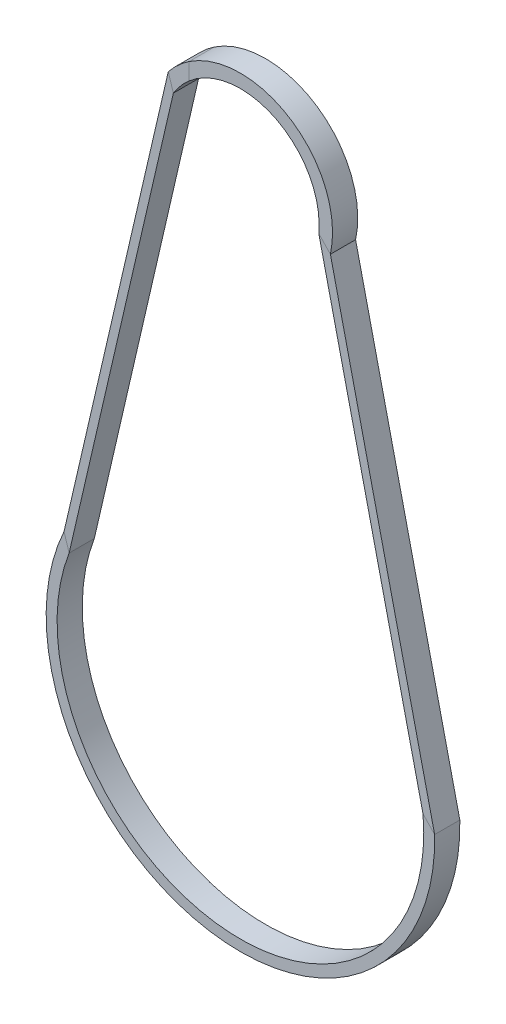
SolidWorks part; units mm, degrees
ref_plane "Front Plane" through (0, 0, 0) normal (0, 0, 1) x (1, 0, 0)
ref_plane "Top Plane" through (0, 0, 0) normal (0, 1, 0) x (1, 0, 0)
ref_plane "Right Plane" through (0, 0, 0) normal (1, 0, 0) x (0, 0, -1)
sketch "Sketch2" plane through (0, 0, 0) normal (0, 0, 1) x (1, 0, 0)
  line L0 (0, 0) -> (1, 0) construction
  line L1 (0, 0) -> (0, 1) construction
  line L2 (10.3864, 8.148) -> (22.7969, -45.48)
  line L3 (-15.8751, -45.48) -> (-3.4646, 8.148)
  arc A0 (-3.4646, 8.148) -> (10.3864, 8.148) centre (3.4609, 6.5453) cw
  arc A1 (22.7969, -45.48) -> (-15.8751, -45.48) centre (3.4609, -49.9547) cw
sketch "Sketch3" plane through (0, 0, 0) normal (0, 0, 1) x (1, 0, 0)
  line L0 (3.4609, 1) -> (3.4609, 13.6538)
  arc A1 (10.3864, 8.148) -> (-3.4646, 8.148) centre (3.4609, 6.5453) ccw construction
ref_plane "Plane2" through (-2.65, 0, 0) normal (1, 0, 0) x (0, 0, -1)
sketch "Sketch5" plane through (-2.65, 0, 0) normal (1, 0, 0) x (0, 0, -1)
  line L0 (0, 1) -> (0, 13.6538) construction
  line L1 (0, 13.6538) -> (3, 13.6538)
  line L2 (0, 13.6538) -> (0, 15.6538)
  line L3 (0, 15.6538) -> (3, 15.6538)
  line L4 (3, 13.6538) -> (3, 15.6538)
  line L5 (0, 13.6538) -> (0, 8.148) construction
  dimension "D1" = 3
  dimension "D2" = 2
sweep "Sweep2" add profiles "Sketch5" path "Sketch2"
